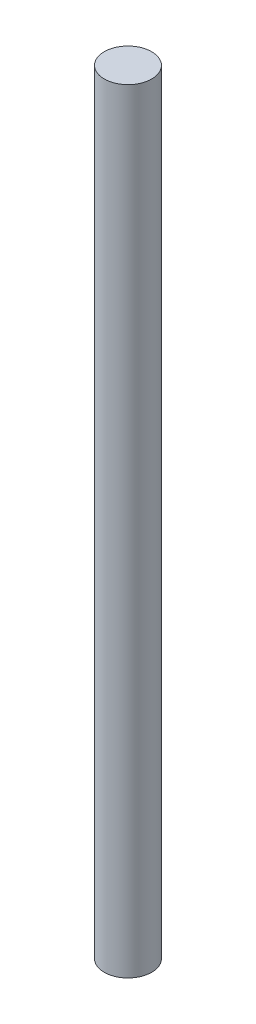
SolidWorks part; units mm, degrees
material "Chrome Stainless Steel"
ref_plane "Front Plane" through (0, 0, 0) normal (0, 0, 1) x (1, 0, 0)
ref_plane "Top Plane" through (0, 0, 0) normal (0, 1, 0) x (1, 0, 0)
ref_plane "Right Plane" through (0, 0, 0) normal (1, 0, 0) x (0, 0, -1)
sketch "Sketch1" plane through (0, 0, 0) normal (0, 1, 0) x (1, 0, 0)
  circle A0 centre (0, 0) radius 1.5
  dimension "D1" = 3
extrude "Boss-Extrude1" add sketch "Sketch1" along normal blind 49
